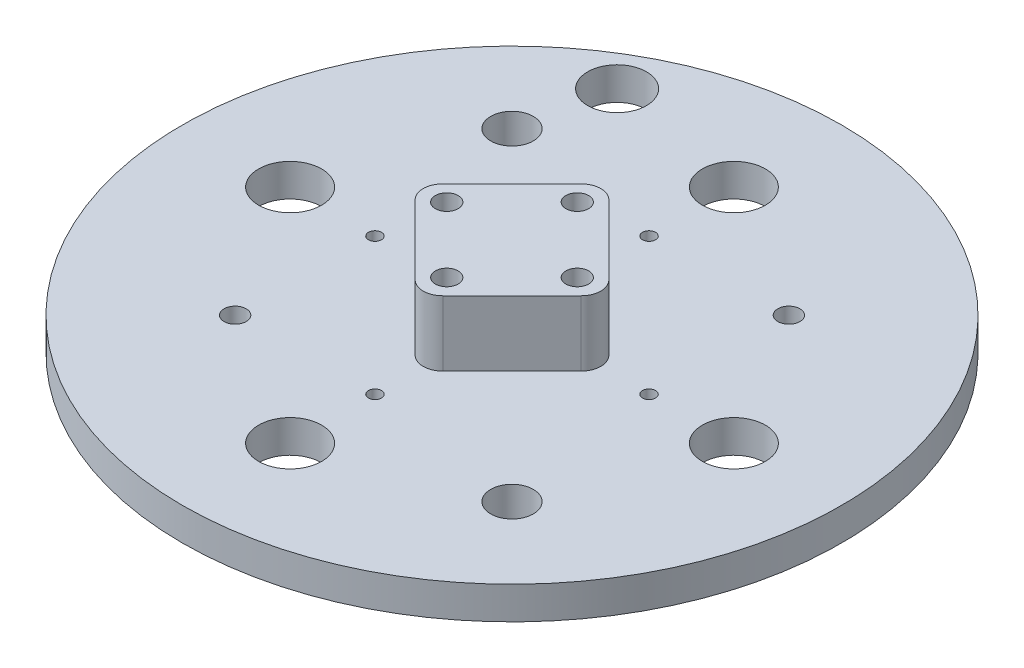
SolidWorks part; units mm, degrees
ref_plane "Front Plane" through (0, 0, 0) normal (0, 0, 1) x (1, 0, 0)
ref_plane "Top Plane" through (0, 0, 0) normal (0, 1, 0) x (1, 0, 0)
ref_plane "Right Plane" through (0, 0, 0) normal (1, 0, 0) x (0, 0, -1)
sketch "Sketch1" plane through (0, 0, 0) normal (0, 1, 0) x (1, 0, 0)
  circle A0 centre (0, 0) radius 50.5
  dimension "D1" = 101
extrude "Boss-Extrude1" add sketch "Sketch1" along normal blind 5
sketch "Sketch3" plane through (0, 5, 0) normal (0, 1, 0) x (1, 0, 0)
  line L0 (0, 0) -> (10, 0) construction
  line L1 (0, -14.8492) -> (14.8492, 0)
  line L2 (0, -14.8492) -> (-14.8492, 0)
  line L3 (14.8492, 0) -> (0, 14.8492)
  line L4 (-14.8492, 0) -> (0, 14.8492)
  line L5 (0, -14.8492) -> (0, 14.8492) construction
  line L6 (14.8492, 0) -> (-14.8492, 0) construction
  circle A0 centre (10, 0) radius 1.75
  circle A2 centre (0, -10) radius 1.75
  circle A3 centre (-10, 0) radius 1.75
  circle A4 centre (0, 10) radius 1.75
  point P13 (0, 0)
  dimension "D2" = 3.5
  dimension "D3" = 4
  dimension "D1" = 10
  dimension "D4" = 21
extrude "Boss-Extrude2" add sketch "Sketch3" along normal blind 10
pattern_circular "CirPattern1" [suppressed] count 4 over 360
sketch "Sketch4" plane through (0, 5, 0) normal (0, 1, 0) x (1, 0, 0)
  line L0 (-35.7089, -35.7089) -> (35.7089, 35.7089) construction
  line L1 (0, 0) -> (50.5, 0) construction
  line L2 (0, 0) -> (-35.7089, 35.7089) construction
  line L19 (34.2947, 23.6881) -> (23.6881, 34.2947) construction
  circle A0 centre (0, 0) radius 50.5 construction
  circle A2 centre (21.2132, 21.2132) radius 1.7
  circle A4 centre (-21.2132, -21.2132) radius 1.7
  circle A5 centre (-24.7487, 24.7487) radius 3.2639
  circle A6 centre (24.7487, -24.7487) radius 3.2639
  point P4 (0, 0)
  point P11 (34.2947, 23.6881)
  dimension "D5" = 3.4
  dimension "D8" = 6.5278
  dimension "D9" = 35
  dimension "D2" = 11
  dimension "D1" = 45
  dimension "D3" = 30
  dimension "D7" = 41
extrude "Cut-Extrude2" cut sketch "Sketch4" against normal through all
sketch "Sketch5" plane through (0, 5, 0) normal (0, 1, 0) x (1, 0, 0)
  circle A0 centre (0, 0) radius 34 construction
  circle A1 centre (34, 0) radius 4.826
  circle A2 centre (0, 34) radius 4.826
  circle A3 centre (-34, 0) radius 4.826
  circle A4 centre (0, -34) radius 4.826
  dimension "D1" = 68
  dimension "D2" = 9.652
extrude "Cut-Extrude3" cut sketch "Sketch5" against normal through all
sketch "Sketch6" plane through (0, 5, 0) normal (0, 1, 0) x (1, 0, 0)
  line L0 (0, 0) -> (14.8492, 14.8492) construction
  line L1 (0, 0) -> (69.3461, 0) construction
  circle A0 centre (0, 0) radius 21 construction
  circle A1 centre (0, 21) radius 1
  circle A2 centre (-21, 0) radius 1
  circle A3 centre (21, 0) radius 1
  circle A4 centre (0, -21) radius 1
  point P22 (0, 0)
  dimension "D1" = 42
  dimension "D2" = 2
  dimension "D4" = 45
extrude "Cut-Extrude4" cut sketch "Sketch6" against normal blind 10
draft "Draft1" [suppressed] draft angle 10 parameters "D1"=10
fillet "Fillet1" radius 3 4 edges at (0, 10, -14.8492) (14.8492, 10, 0) (-14.8492, 10, 0) (0, 10, 14.8492)
sketch "Sketch7" plane through (0, 0, 0) normal (0, 1, 0) x (1, 0, 0)
  line L0 (0, 0) -> (0, 69.0165) construction
  line L1 (0, 0) -> (-22, 38.1051) construction
  circle A0 centre (-22, 38.1051) radius 4.5
  dimension "D1" = 9
  dimension "D2" = 30
  dimension "D3" = 44
extrude "Cut-Extrude5" cut sketch "Sketch7" along normal through all
